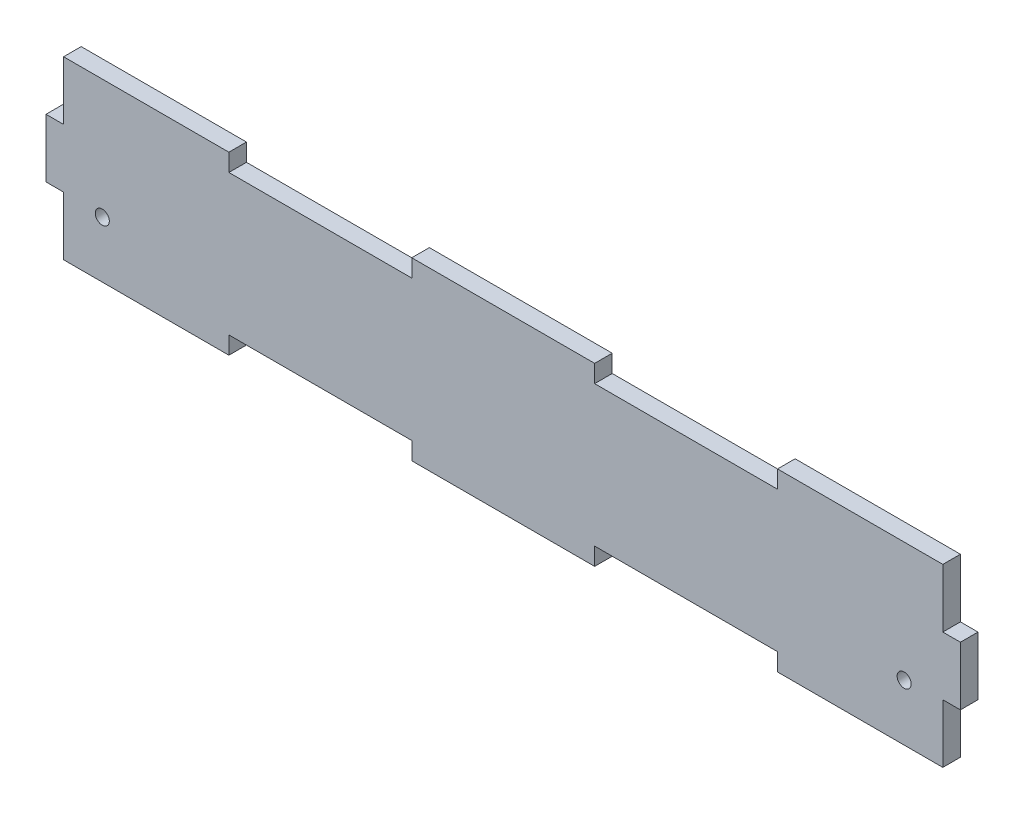
SolidWorks part; units mm, degrees
ref_plane "Alzado" through (0, 0, 0) normal (0, 0, 1) x (1, 0, 0)
ref_plane "Planta" through (0, 0, 0) normal (0, 1, 0) x (1, 0, 0)
ref_plane "Vista lateral" through (0, 0, 0) normal (1, 0, 0) x (0, 0, -1)
sketch "Croquis1" plane through (0, 0, 0) normal (0, 0, 1) x (1, 0, 0)
  line L0 (0, 33.3333) -> (5, 33.3333)
  line L1 (5, 0) -> (52, 0)
  line L2 (0, 16.6667) -> (0, 33.3333)
  line L3 (5, 50) -> (52, 50)
  line L4 (260, 16.6667) -> (260, 33.3333)
  line L5 (5, 33.3333) -> (5, 16.6667) construction
  line L6 (5, 16.6667) -> (0, 16.6667)
  line L7 (130, 50) -> (130, 31.9566) construction
  line L8 (0, 25) -> (30.953, 25) construction
  line L9 (5, 33.3333) -> (5, 50)
  line L10 (5, 16.6667) -> (5, 0)
  line L11 (0, 0) -> (5, 0) construction
  line L12 (0, 0) -> (0, 16.6667) construction
  line L13 (255, 16.6667) -> (255, 0)
  line L14 (255, 16.6667) -> (260, 16.6667)
  line L15 (260, 33.3333) -> (255, 33.3333)
  line L16 (255, 33.3333) -> (255, 50)
  line L17 (52, 0) -> (52, 5)
  line L18 (52, 5) -> (104, 5)
  line L19 (104, 5) -> (104, 0)
  line L20 (156, 5) -> (156, 0)
  line L21 (208, 5) -> (156, 5)
  line L22 (208, 0) -> (208, 5)
  line L23 (208, 50) -> (208, 45)
  line L24 (208, 45) -> (156, 45)
  line L25 (156, 45) -> (156, 50)
  line L26 (104, 45) -> (104, 50)
  line L27 (52, 45) -> (104, 45)
  line L28 (52, 50) -> (52, 45)
  line L29 (104, 50) -> (156, 50)
  line L30 (208, 50) -> (255, 50)
  line L31 (104, 0) -> (156, 0)
  line L32 (208, 0) -> (255, 0)
  circle A0 centre (16, 16) radius 2
  circle A1 centre (244, 16) radius 2
  dimension "D3" = 4
  dimension "D1" = 260
  dimension "D2" = 50
  dimension "D4" = 16.6667
  dimension "D5" = 5
  dimension "D6" = 52
  dimension "D7" = 52
  dimension "D8" = 5
  dimension "D9" = 16
  dimension "D10" = 16
extrude "Saliente-Extruir1" add sketch "Croquis1" along normal blind 5
